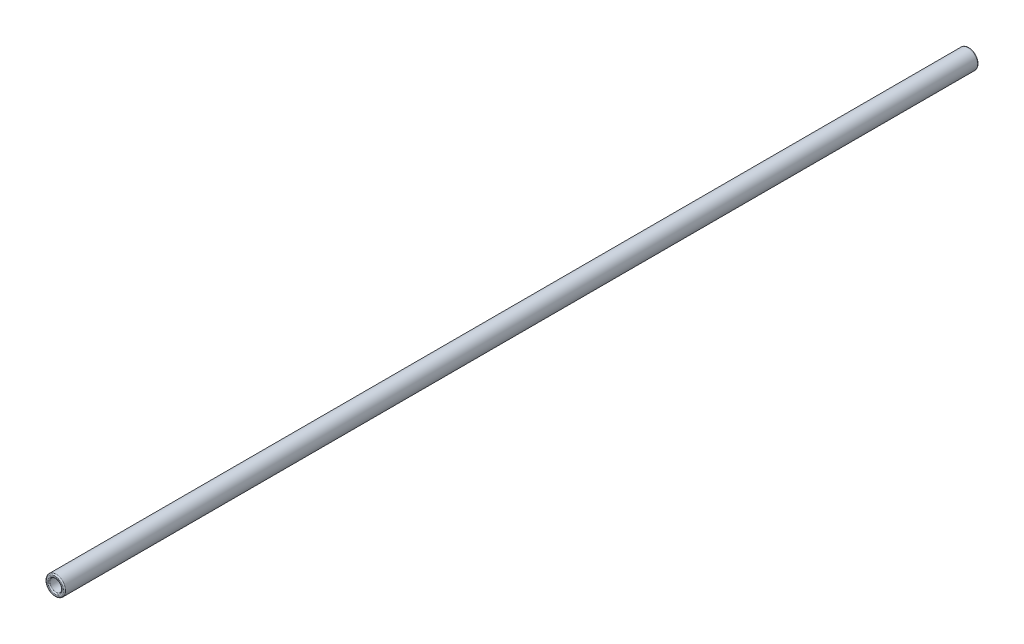
SolidWorks part; units mm, degrees
material "Polyurethane Foam Flexible"
ref_plane "Front Plane" through (0, 0, 0) normal (0, 0, 1) x (1, 0, 0)
ref_plane "Top Plane" through (0, 0, 0) normal (0, 1, 0) x (1, 0, 0)
ref_plane "Right Plane" through (0, 0, 0) normal (1, 0, 0) x (0, 0, -1)
sketch "Sketch2" plane through (0, 0, 0) normal (0, 0, 1) x (1, 0, 0)
  circle A0 centre (0, 0) radius 8.636
  circle A1 centre (0, 0) radius 5.461
  dimension "D1" = 17.272
  dimension "D2" = 3.175
extrude "Boss-Extrude1" add sketch "Sketch2" along normal blind 820 contours A0
fillet "Fillet1" radius 1.016 4 edges at (5.461, 0, 820) (8.636, 0, 820) (5.461, 0, 0) (8.636, 0, 0)
